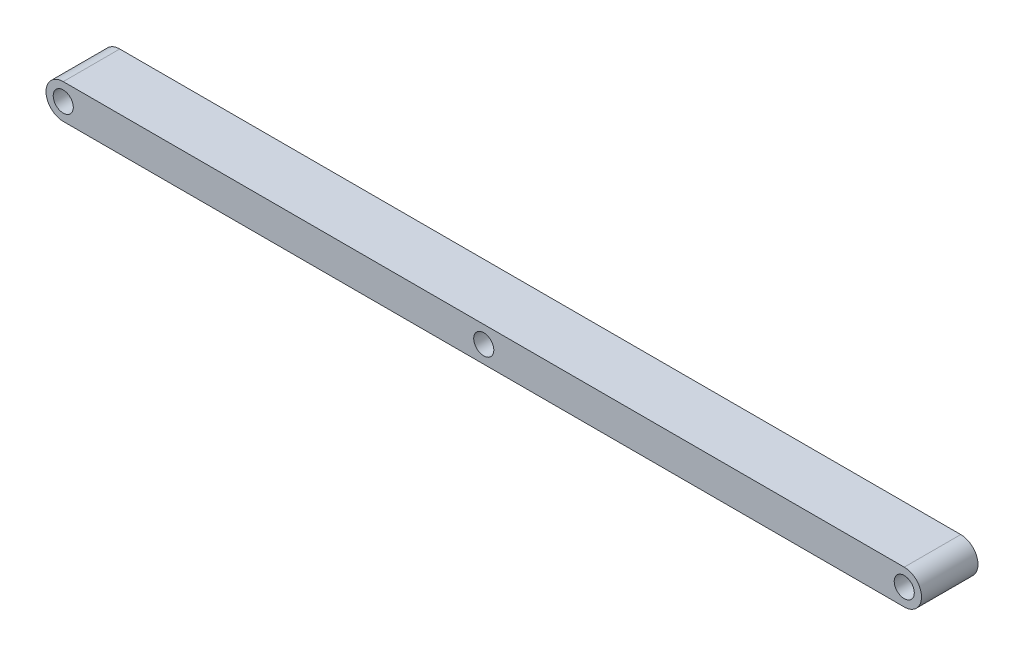
SolidWorks part; units mm, degrees
ref_plane "前基準面" through (0, 0, 0) normal (0, 0, 1) x (1, 0, 0)
ref_plane "上基準面" through (0, 0, 0) normal (0, 1, 0) x (1, 0, 0)
ref_plane "右基準面" through (0, 0, 0) normal (1, 0, 0) x (0, 0, -1)
sketch "草圖1" plane through (0, 0, 0) normal (0, 0, 1) x (1, 0, 0)
  line L0 (-41.9264, 0) -> (92.0736, 0) construction
  line L1 (-41.9264, 2.75) -> (92.0736, 2.75)
  line L2 (-41.9264, -2.75) -> (92.0736, -2.75)
  arc A0 (-41.9264, 2.75) -> (-41.9264, -2.75) centre (-41.9264, 0) ccw
  arc A1 (92.0736, -2.75) -> (92.0736, 2.75) centre (92.0736, 0) ccw
  circle A2 centre (92.0736, 0) radius 1.6
  circle A3 centre (-41.9264, 0) radius 1.6
  circle A4 centre (25.0736, 0) radius 1.6
  point P3 (25.0736, 0)
  dimension "D3" = 3.2
  dimension "D4" = 3.2
  dimension "D5" = 3.2
  dimension "D1" = 134
  dimension "D2" = 5.5
extrude "填料-伸長1" add sketch "草圖1" along normal blind 9
